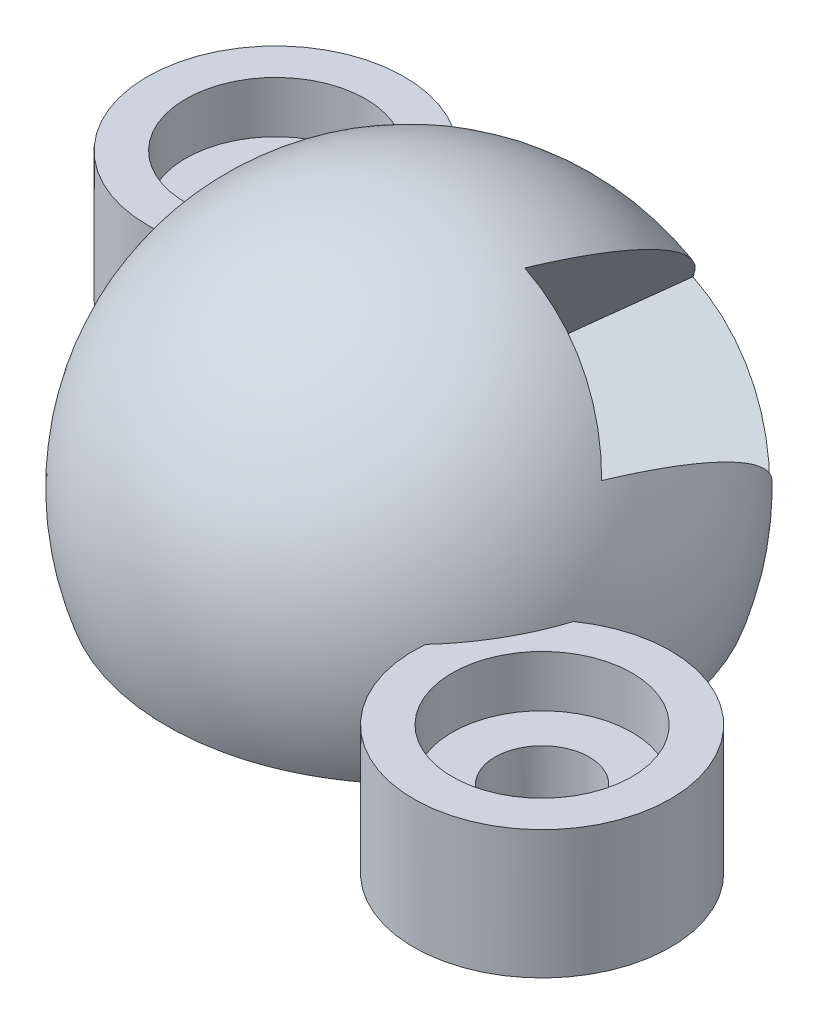
SolidWorks part; units mm, degrees
other "Compression Link 2 Fixed Ball Retainer"
other "Compression Link 2 Fixed Ball Retainer Left"
ref_plane "Front Plane" through (0, 0, 0) normal (0, 0, 1) x (1, 0, 0)
ref_plane "Top Plane" through (0, 0, 0) normal (0, 1, 0) x (1, 0, 0)
ref_plane "Right Plane" through (0, 0, 0) normal (1, 0, 0) x (0, 0, -1)
sketch3d "Retainer Dome axis line"
  line L0 (-62.6314, -73, 30.9808) -> (-79.9519, -73, 20.9808) construction
ref_axis "Retainer Dome axis" through (-62.6314, -73, 30.9808) along (-0.866, 0, -0.5)
sketch3d "Retainer Dome Sketch datum points"
  point P0 (-71.2917, -73, 25.9808)
  point P1 (-76.2917, -73, 34.641)
  point P2 (-79.9519, -73, 20.9808)
ref_plane "Retainer Dome Sketch plane" through (0, -73, 0) normal (0, -1, 0) x (-1, 0, 0)
sketch "Retainer Dome Sketch" plane through (0, -73, 0) normal (0, -1, 0) x (-1, 0, 0)
  line L0 (76.4878, -22.9808) -> (66.0955, -28.9808)
  arc A0 (66.0955, -28.9808) -> (76.4878, -22.9808) centre (71.2917, -25.9808) ccw
revolve "Retainer Dome" add sketch "Retainer Dome Sketch" angle 360 about axis through (-62.6314, -73, 30.9808) along (-0.866, 0, -0.5)
sketch3d "Dome Trim Sketch datum points"
  point P0 (-61.7295, -71, 23.4186)
  point P1 (-66.7295, -71, 32.0788)
  point P2 (-61.7295, -61, 23.4186)
ref_plane "Dome Trim Sketch plane" through (-36.1566, 0, -20.875) normal (-0.866, 0, -0.5) x (-0.5, 0, 0.866)
sketch "Dome Trim Sketch" plane through (-36.1566, 0, -20.875) normal (-0.866, 0, -0.5) x (-0.5, 0, 0.866)
  line L0 (51.1458, -71) -> (65.1458, -71)
  line L1 (65.1458, -71) -> (65.1458, -66)
  line L2 (65.1458, -66) -> (51.1458, -66)
  line L3 (51.1458, -66) -> (51.1458, -71)
extrude "Dome Trim" cut sketch "Dome Trim Sketch" along normal blind 14
sketch3d "Retainer Feature 3 profile datum points"
  point P0 (-63.9304, -71, 30.2308)
  point P1 (-53.9304, -71, 30.2308)
  point P2 (-63.9304, -71, 40.2308)
ref_plane "Retainer Feature 3 profile plane" through (0, -71, 0) normal (0, -1, 0) x (-1, 0, 0)
sketch "Retainer Feature 3 profile" plane through (0, -71, 0) normal (0, -1, 0) x (-1, 0, 0)
  circle A0 centre (63.9304, -30.2308) radius 3
extrude "Retainer Feature 3" add sketch "Retainer Feature 3 profile" along normal blind 3
sketch3d "Retainer Feature 4 profile datum points"
  point P0 (-78.6529, -71, 21.7308)
  point P1 (-68.6529, -71, 21.7308)
  point P2 (-78.6529, -71, 31.7308)
ref_plane "Retainer Feature 4 profile plane" through (0, -71, 0) normal (0, -1, 0) x (-1, 0, 0)
sketch "Retainer Feature 4 profile" plane through (0, -71, 0) normal (0, -1, 0) x (-1, 0, 0)
  circle A0 centre (78.6529, -21.7308) radius 3
extrude "Retainer Feature 4" add sketch "Retainer Feature 4 profile" along normal blind 3
sketch3d "Spherical Seat axis line"
  line L0 (-62.6314, -73, 30.9808) -> (-79.9519, -73, 20.9808) construction
ref_axis "Spherical Seat axis" through (-62.6314, -73, 30.9808) along (-0.866, 0, -0.5)
sketch3d "Spherical Seat Sketch datum points"
  point P0 (-71.2917, -73, 25.9808)
  point P1 (-76.2917, -73, 34.641)
  point P2 (-79.9519, -73, 20.9808)
ref_plane "Spherical Seat Sketch plane" through (0, -73, 0) normal (0, -1, 0) x (-1, 0, 0)
sketch "Spherical Seat Sketch" plane through (0, -73, 0) normal (0, -1, 0) x (-1, 0, 0)
  line L0 (74.0196, -24.4058) -> (68.5637, -27.5558)
  arc A0 (68.5637, -27.5558) -> (74.0196, -24.4058) centre (71.2917, -25.9808) ccw
revolve "Spherical Seat" cut sketch "Spherical Seat Sketch" angle 360 about axis through (-62.6314, -73, 30.9808) along (-0.866, 0, -0.5)
sketch3d "Retainer Feature 6 profile datum points"
  point P0 (-63.9304, -70, 30.2308)
  point P1 (-53.9304, -70, 30.2308)
  point P2 (-63.9304, -70, 40.2308)
ref_plane "Retainer Feature 6 profile plane" through (0, -70, 0) normal (0, -1, 0) x (-1, 0, 0)
sketch "Retainer Feature 6 profile" plane through (0, -70, 0) normal (0, -1, 0) x (-1, 0, 0)
  circle A0 centre (63.9304, -30.2308) radius 1.1
extrude "Retainer Feature 6" cut sketch "Retainer Feature 6 profile" along normal blind 4.25
sketch3d "Retainer Feature 7 profile datum points"
  point P0 (-63.9304, -72.8, 30.2308)
  point P1 (-53.9304, -72.8, 30.2308)
  point P2 (-63.9304, -72.8, 40.2308)
ref_plane "Retainer Feature 7 profile plane" through (0, -72.8, 0) normal (0, -1, 0) x (-1, 0, 0)
sketch "Retainer Feature 7 profile" plane through (0, -72.8, 0) normal (0, -1, 0) x (-1, 0, 0)
  circle A0 centre (63.9304, -30.2308) radius 2.1
extrude "Retainer Feature 7" cut sketch "Retainer Feature 7 profile" along normal blind 1.45
sketch3d "Retainer Feature 8 profile datum points"
  point P0 (-78.6529, -70, 21.7308)
  point P1 (-68.6529, -70, 21.7308)
  point P2 (-78.6529, -70, 31.7308)
ref_plane "Retainer Feature 8 profile plane" through (0, -70, 0) normal (0, -1, 0) x (-1, 0, 0)
sketch "Retainer Feature 8 profile" plane through (0, -70, 0) normal (0, -1, 0) x (-1, 0, 0)
  circle A0 centre (78.6529, -21.7308) radius 1.1
extrude "Retainer Feature 8" cut sketch "Retainer Feature 8 profile" along normal blind 4.25
sketch3d "Retainer Feature 9 profile datum points"
  point P0 (-78.6529, -72.8, 21.7308)
  point P1 (-68.6529, -72.8, 21.7308)
  point P2 (-78.6529, -72.8, 31.7308)
ref_plane "Retainer Feature 9 profile plane" through (0, -72.8, 0) normal (0, -1, 0) x (-1, 0, 0)
sketch "Retainer Feature 9 profile" plane through (0, -72.8, 0) normal (0, -1, 0) x (-1, 0, 0)
  circle A0 centre (78.6529, -21.7308) radius 2.1
extrude "Retainer Feature 9" cut sketch "Retainer Feature 9 profile" along normal blind 1.45
sketch3d "Middle Right Fixed Compression Ball Retainer 1 Angular Clearance Sketch 21 datum points"
  point P0 (-71.2917, -73, 25.9808)
  point P1 (-69.2533, -78.3859, 34.1562)
  point P2 (-78.4932, -79.4818, 23.5061)
ref_plane "Middle Right Fixed Compression Ball Retainer 1 Angular Clearance Sketch 21 plane" through (-14.2547, 11.5703, 11.1766) normal (0.6632, -0.5383, -0.52) x (-0.4037, 0.3277, -0.8542)
sketch "Middle Right Fixed Compression Ball Retainer 1 Angular Clearance Sketch 21" plane through (-14.2547, 11.5703, 11.1766) normal (0.6632, -0.5383, -0.52) x (-0.4037, 0.3277, -0.8542)
  line L0 (-14.8193, -98.8621) -> (-20.9448, -100.7163)
  line L1 (-20.9448, -100.7163) -> (-19.8439, -104.3533)
  line L2 (-19.8439, -104.3533) -> (-13.7184, -102.4991)
  line L3 (-13.7184, -102.4991) -> (-14.8193, -98.8621)
extrude "Retainer Feature 12" cut sketch "Middle Right Fixed Compression Ball Retainer 1 Angular Clearance Sketch 21" along normal blind 10
sketch3d "Mirror1 profile datum points"
  point P0 (0, 0, 0)
  point P1 (10, 0, 0)
  point P2 (0, 0, 10)
ref_plane "Mirror1 profile plane" through (0, 0, 0) normal (0, -1, 0) x (-1, 0, 0)
mirror "Mirror1" about plane through (0, 0, 0) normal (0, -1, 0) of bodies 110
delete or keep bodies "Remove1" type delete bodies bodies 110
